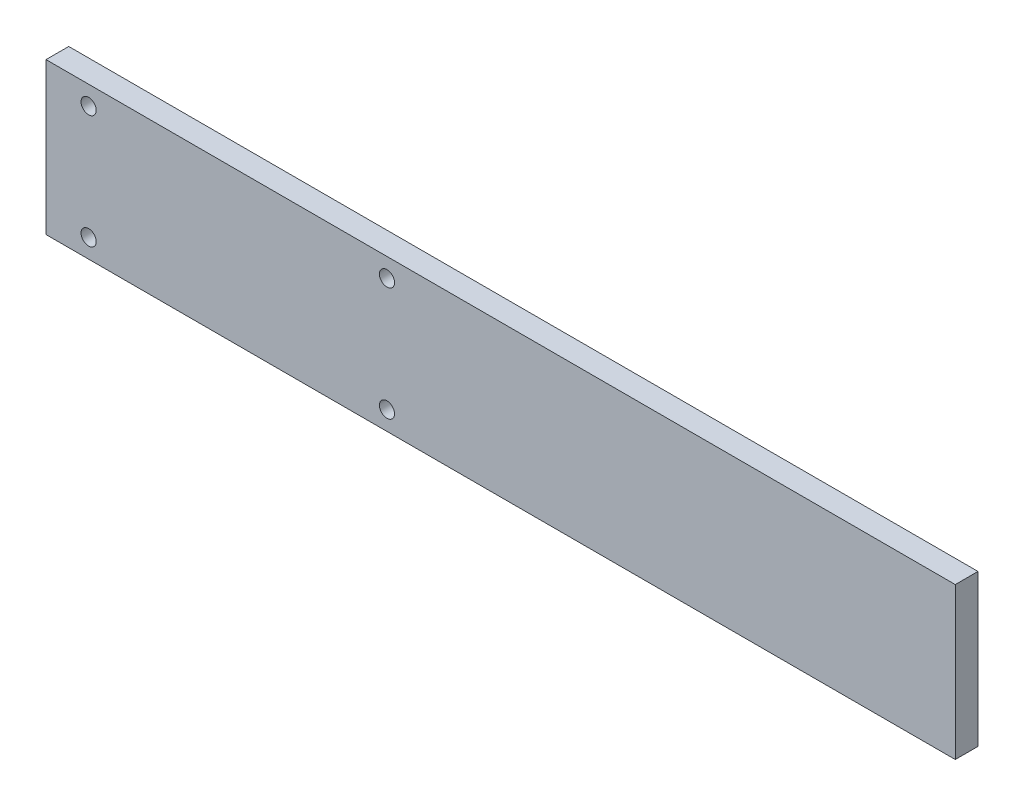
SolidWorks part; units mm, degrees
ref_plane "Front Plane" through (0, 0, 0) normal (0, 0, 1) x (1, 0, 0)
ref_plane "Top Plane" through (0, 0, 0) normal (0, 1, 0) x (1, 0, 0)
ref_plane "Right Plane" through (0, 0, 0) normal (1, 0, 0) x (0, 0, -1)
sketch "Sketch1" plane through (0, 0, 0) normal (0, 0, 1) x (1, 0, 0)
  line L1 (1524, 254) -> (-1524, 254)
  line L2 (1524, 254) -> (1524, -254)
  line L3 (1524, -254) -> (-1524, -254)
  line L4 (-1524, 254) -> (-1524, -254)
  line L5 (1524, 254) -> (-1524, -254) construction
  line L6 (1524, -254) -> (-1524, 254) construction
  point P0 (0, 0)
  dimension "D1" = 508
  dimension "D2" = 3048
extrude "Boss-Extrude1" add sketch "Sketch1" along normal blind 76.2
sketch "Sketch2" plane through (0, 0, 76.2) normal (0, 0, 1) x (1, 0, 0)
  line L0 (-1524, 0) -> (0, 0) construction
  line L1 (-1524, 254) -> (-1524, -254) construction
  line L2 (0, 0) -> (-762, 0) construction
  line L3 (-762, 0) -> (-381, 0) construction
  line L4 (-381, 0) -> (-381, 254) construction
  line L5 (1524, 254) -> (-1524, 254) construction
  line L6 (-381, 254) -> (-381, 0) construction
  line L7 (-381, 0) -> (-381, -254) construction
  line L8 (-1524, -254) -> (1524, -254) construction
  line L9 (-381, -254) -> (-381, -127) construction
  line L10 (-1524, 0) -> (-381, 0) construction
  line L11 (-381, 0) -> (-952.5, 0) construction
  line L12 (-952.5, 0) -> (-1524, 0) construction
  line L13 (-1524, 0) -> (-1238.25, 0) construction
  line L14 (-1238.25, 0) -> (-1381.125, 0) construction
  line L15 (-1381.125, 0) -> (-1381.125, 254) construction
  line L16 (-1381.125, 254) -> (-1381.125, -254) construction
  line L17 (-381, -190.5) -> (-1381.125, -190.5) construction
  circle A0 centre (-381, -190.5) radius 25.4
  circle A1 centre (-1381.125, -190.5) radius 25.4
  circle A2 centre (-381, 190.5) radius 25.4
  circle A3 centre (-1381.125, 190.5) radius 25.4
  dimension "D1" = 50.8
  dimension "D2" = 50.8
extrude "Cut-Extrude1" cut sketch "Sketch2" against normal through all
